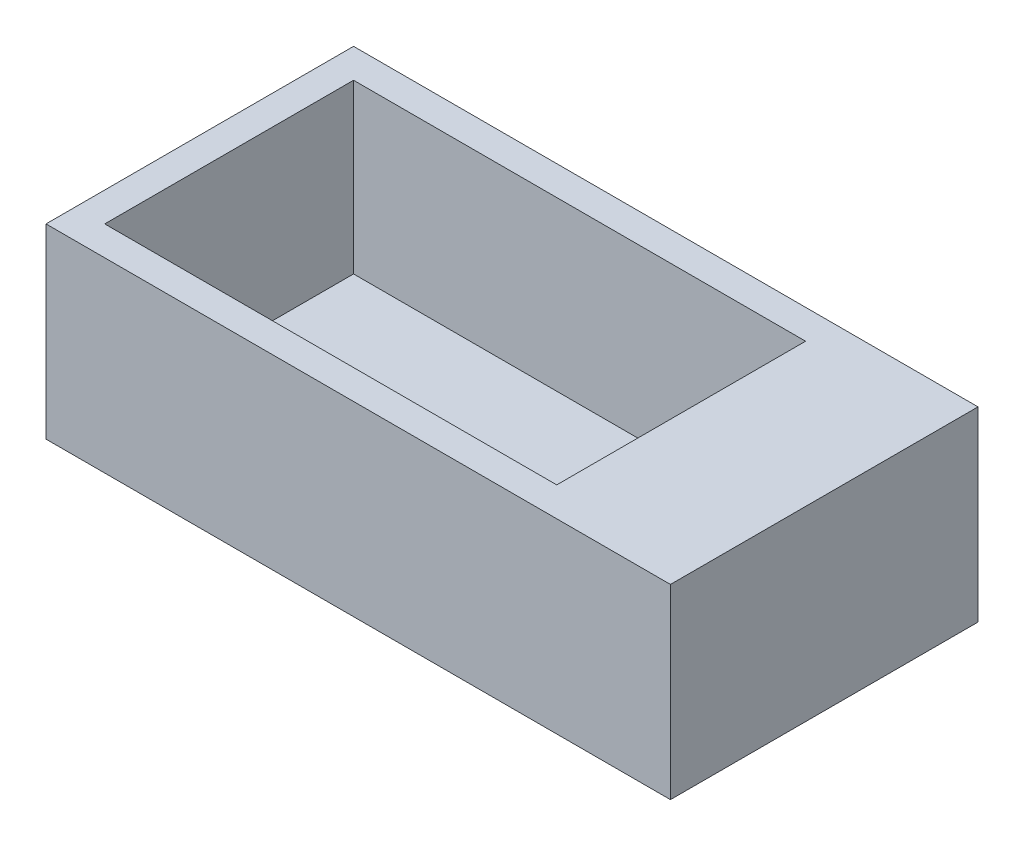
SolidWorks part; units mm, degrees
ref_plane "Plano frontal" through (0, 0, 0) normal (0, 0, 1) x (1, 0, 0)
ref_plane "Plano superior" through (0, 0, 0) normal (0, 1, 0) x (1, 0, 0)
ref_plane "Plano direito" through (0, 0, 0) normal (1, 0, 0) x (0, 0, -1)
sketch "Esboço1" plane through (0, 0, 0) normal (0, 1, 0) x (1, 0, 0)
  line L0 (-30.35, 0) -> (18.15, 0) construction
  line L5 (-33.5, -16.5) -> (33.5, -16.5)
  line L6 (-33.5, -16.5) -> (-33.5, 16.5)
  line L7 (-33.5, 16.5) -> (33.5, 16.5)
  line L8 (33.5, -16.5) -> (33.5, 16.5)
  line L9 (-33.5, -16.5) -> (33.5, 16.5) construction
  line L10 (-33.5, 16.5) -> (33.5, -16.5) construction
  line L11 (-30.35, -13.35) -> (30.35, -13.35)
  line L12 (-30.35, -13.35) -> (-30.35, 13.35)
  line L13 (-30.35, 13.35) -> (30.35, 13.35)
  line L14 (30.35, -13.35) -> (30.35, 13.35)
  line L15 (-30.35, -13.35) -> (30.35, 13.35) construction
  line L16 (-30.35, 13.35) -> (30.35, -13.35) construction
  line L17 (18.15, 13.35) -> (18.15, -13.35)
  point P0 (0, 0)
  point P6 (0, 0)
  dimension "D1" = 67
  dimension "D2" = 33
  dimension "D3" = 3.15
  dimension "D4" = 26.7
  dimension "D5" = 48.5
extrude "Ressalto-extrusão4" add sketch "Esboço1" along normal blind 20 contours L13 L17 L11 L14 | L5 L8 L7 L6 L14 L11 L12 L13
sketch "Esboço3" plane through (0, 0, 0) normal (0, 1, 0) x (1, 0, 0)
  line L1 (-30.35, 13.35) -> (18.15, 13.35)
  line L2 (-30.35, 13.35) -> (-30.35, -13.35)
  line L3 (-30.35, -13.35) -> (18.15, -13.35)
  line L4 (18.15, 13.35) -> (18.15, -13.35)
extrude "Ressalto-extrusão5" add sketch "Esboço3" along normal blind 2
sketch "Esboço4" plane through (0, 0, 0) normal (1, 0, 0) x (0, 0, -1)
  line L0 (0, 2) -> (0, 10.75) construction
  line L1 (13.35, 2) -> (-13.35, 2) construction
  line L2 (6.35, 10.75) -> (-6.35, 10.75) construction
  circle A4 centre (6.35, 10.75) radius 3.9
  circle A5 centre (6.35, 10.75) radius 2.83
  circle A6 centre (-6.35, 10.75) radius 3.9
  circle A7 centre (-6.35, 10.75) radius 2.83
  point P5 (0, 0)
  point P16 (0, 0)
  dimension "D6" = 7.8
  dimension "D7" = 5.66
  dimension "D1" = 8.75
  dimension "D2" = 12.7
extrude "Ressalto-extrusão9" add sketch "Esboço4" against normal blind 2 from surface at 18.15 contours A4 A5 | A7 starting at face at (18.15, 11, 0)
